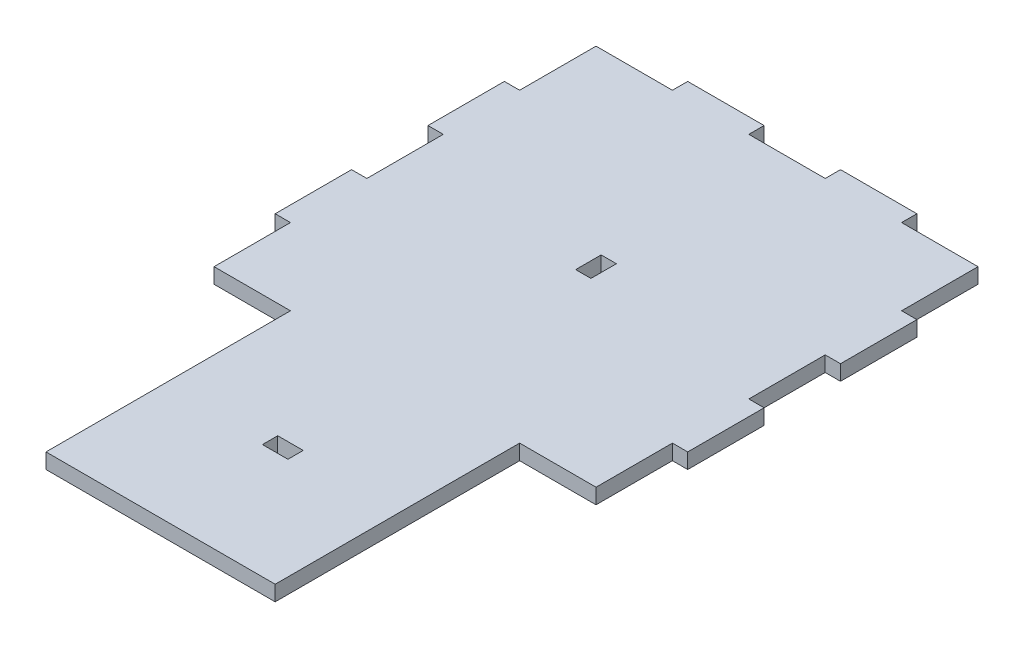
SolidWorks part; units mm, degrees
ref_plane "Plano frontal" through (0, 0, 0) normal (0, 0, 1) x (1, 0, 0)
ref_plane "Plano superior" through (0, 0, 0) normal (0, 1, 0) x (1, 0, 0)
ref_plane "Plano direito" through (0, 0, 0) normal (1, 0, 0) x (0, 0, -1)
sketch "Esboço1" plane through (0, 0, 0) normal (0, 1, 0) x (1, 0, 0)
  line L1 (0, 0) -> (150, 0)
  line L2 (0, 0) -> (0, 150)
  line L3 (0, 150) -> (150, 150)
  line L4 (150, 0) -> (150, 150)
  dimension "D1" = 150
  dimension "D2" = 150
extrude "Ressalto-extrusão1" add sketch "Esboço1" along normal blind 6
sketch "Esboço3" plane through (0, 0, -150) normal (0, 0, -1) x (-1, 0, 0)
  line L0 (-150, 6) -> (0, 6) construction
  line L1 (-150, 0) -> (0, 0) construction
  line L2 (-120, 0) -> (-90, 0)
  line L3 (-120, 0) -> (-120, 6)
  line L4 (-120, 6) -> (-90, 6)
  line L5 (-90, 0) -> (-90, 6)
  line L7 (-60, 0) -> (-30, 0)
  line L8 (-60, 0) -> (-60, 6)
  line L9 (-60, 6) -> (-30, 6)
  line L10 (-30, 0) -> (-30, 6)
  dimension "D1" = 30
  dimension "D2" = 30
  dimension "D3" = 30
  dimension "D4" = 30
  dimension "D5" = 30
extrude "Ressalto-extrusão3" add sketch "Esboço3" along normal blind 6
sketch "Esboço6" plane through (150, 0, 0) normal (1, 0, 0) x (0, 0, -1)
  line L0 (0, 6) -> (150, 6) construction
  line L1 (30, 6) -> (60, 6)
  line L2 (30, 6) -> (30, 0)
  line L3 (30, 0) -> (60, 0)
  line L4 (60, 6) -> (60, 0)
  line L5 (0, 0) -> (150, 0) construction
  line L7 (90, 6) -> (120, 6)
  line L8 (90, 6) -> (90, 0)
  line L9 (90, 0) -> (120, 0)
  line L10 (120, 6) -> (120, 0)
  dimension "D1" = 30
  dimension "D2" = 30
  dimension "D3" = 30
  dimension "D4" = 30
  dimension "D5" = 30
extrude "Ressalto-extrusão6" add sketch "Esboço6" along normal blind 6
sketch "Esboço7" plane through (0, 0, 0) normal (-1, 0, 0) x (0, 0, 1)
  line L0 (-150, 6) -> (0, 6) construction
  line L1 (-120, 6) -> (-90, 6)
  line L2 (-120, 6) -> (-120, 0)
  line L3 (-120, 0) -> (-90, 0)
  line L4 (-90, 6) -> (-90, 0)
  line L5 (-150, 0) -> (0, 0) construction
  line L7 (-30, 6) -> (-60, 6)
  line L8 (-30, 6) -> (-30, 0)
  line L9 (-30, 0) -> (-60, 0)
  line L10 (-60, 6) -> (-60, 0)
  dimension "D1" = 30
  dimension "D2" = 30
  dimension "D3" = 30
  dimension "30" = 30
extrude "Ressalto-extrusão8" add sketch "Esboço7" along normal blind 6
sketch "Esboço9" plane through (0, 0, 0) normal (0, 0, 1) x (1, 0, 0)
  line L0 (0, 6) -> (150, 6) construction
  line L1 (30, 6) -> (120, 6)
  line L2 (30, 6) -> (30, 0)
  line L3 (30, 0) -> (120, 0)
  line L4 (120, 6) -> (120, 0)
  line L5 (0, 0) -> (150, 0) construction
  dimension "D1" = 90
  dimension "D2" = 30
extrude "Ressalto-extrusão9" add sketch "Esboço9" along normal blind 6
sketch "Esboço10" plane through (0, 0, 6) normal (0, 0, 1) x (1, 0, 0)
  line L1 (30, 6) -> (120, 6)
  line L2 (30, 6) -> (30, 0)
  line L3 (30, 0) -> (120, 0)
  line L4 (120, 6) -> (120, 0)
extrude "Ressalto-extrusão10" add sketch "Esboço10" along normal blind 90
sketch "Esboço11" plane through (0, 6, 0) normal (0, 1, 0) x (1, 0, 0)
  line L0 (75, 150) -> (75, -96) construction
  line L1 (90, 150) -> (60, 150) construction
  line L2 (120, -96) -> (30, -96) construction
  line L3 (30, -48) -> (120, -48) construction
  line L4 (30, -96) -> (30, 0) construction
  line L5 (120, -96) -> (120, 0) construction
  line L7 (80, -51) -> (70, -51)
  line L8 (80, -51) -> (80, -45)
  line L9 (80, -45) -> (70, -45)
  line L10 (70, -51) -> (70, -45)
  line L11 (80, -51) -> (70, -45) construction
  line L12 (80, -45) -> (70, -51) construction
  point P12 (75, -48)
  dimension "D1" = 10
  dimension "D2" = 6
extrude "Corte-extrusão1" cut sketch "Esboço11" against normal through all
sketch "Esboço12" plane through (0, 6, 0) normal (0, 1, 0) x (1, 0, 0)
  line L0 (0, 75) -> (150, 75) construction
  line L1 (0, 90) -> (0, 60) construction
  line L2 (150, 60) -> (150, 90) construction
  line L3 (75, 150) -> (75, 0) construction
  line L4 (90, 150) -> (60, 150) construction
  line L6 (78, 70) -> (72, 70)
  line L7 (78, 70) -> (78, 80)
  line L8 (78, 80) -> (72, 80)
  line L9 (72, 70) -> (72, 80)
  line L10 (78, 70) -> (72, 80) construction
  line L11 (78, 80) -> (72, 70) construction
  point P10 (75, 75)
  dimension "D1" = 6
  dimension "D2" = 10
extrude "Corte-extrusão2" cut sketch "Esboço12" against normal through all and the other way through all
